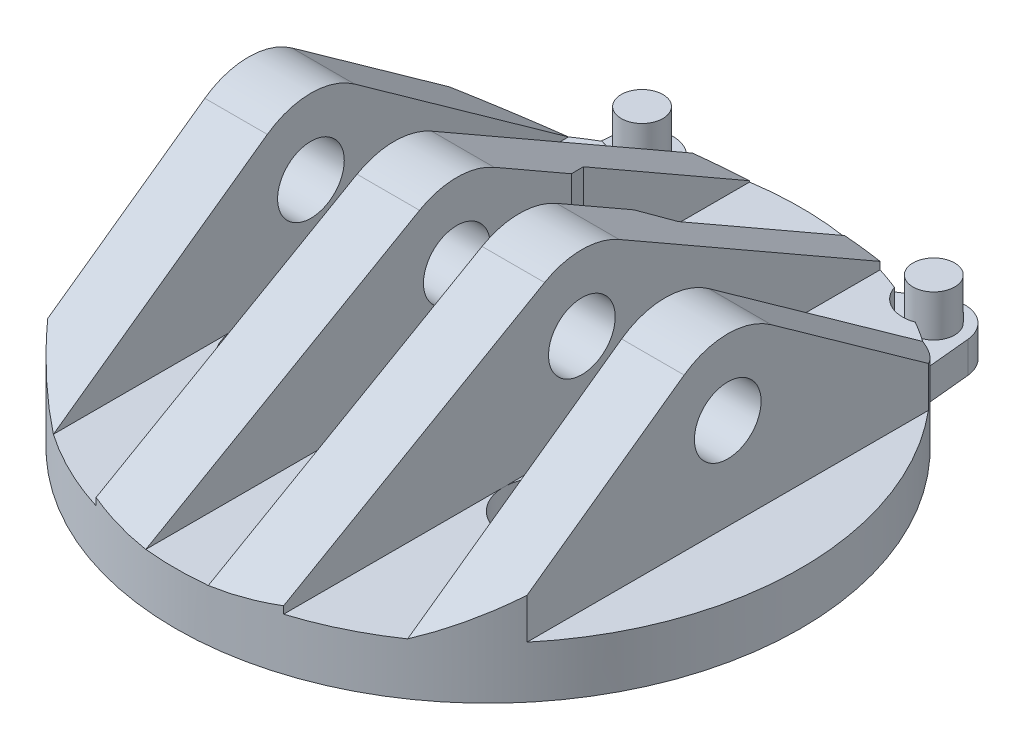
SolidWorks part; units mm, degrees
ref_plane "Front Plane" through (0, 0, 0) normal (0, 0, 1) x (1, 0, 0)
ref_plane "Top Plane" through (0, 0, 0) normal (0, 1, 0) x (1, 0, 0)
ref_plane "Right Plane" through (0, 0, 0) normal (1, 0, 0) x (0, 0, -1)
sketch "Sketch1" plane through (0, 0, 0) normal (0, 1, 0) x (1, 0, 0)
  line L0 (0, 0) -> (0, 15) construction
  line L1 (0, 0) -> (12.9904, -7.5) construction
  line L2 (0, 0) -> (-12.9904, -7.5) construction
  circle A0 centre (0, 0) radius 30
  circle A1 centre (0, 0) radius 15 construction
  circle A2 centre (0, 15) radius 2.1
  circle A3 centre (12.9904, -7.5) radius 2.1
  circle A4 centre (-12.9904, -7.5) radius 2.1
  dimension "D1" = 60
  dimension "D2" = 30
  dimension "D5" = 4.2
  dimension "D3" = 120
  dimension "D4" = 120
extrude "Boss-Extrude1" add sketch "Sketch1" along normal blind 5
sketch "Sketch2" plane through (0, 5, 0) normal (0, 1, 0) x (1, 0, 0)
  line L0 (0, 30) -> (0, -30) construction
  line L5 (17, 11) -> (17, 24.7184)
  line L6 (-3, -29.8496) -> (3, -29.8496)
  line L8 (4.1569, 15) -> (2.0785, 18.6)
  line L9 (2.0785, 18.6) -> (-2.0785, 18.6)
  line L10 (-2.0785, 18.6) -> (-4.1569, 15)
  line L11 (-4.1569, 15) -> (-2.0785, 11.4)
  line L12 (-2.0785, 11.4) -> (2.0785, 11.4)
  line L13 (2.0785, 11.4) -> (4.1569, 15)
  line L14 (-12.9904, -3.3431) -> (-16.5904, -5.4215)
  line L15 (-16.5904, -5.4215) -> (-16.5904, -9.5785)
  line L16 (-16.5904, -9.5785) -> (-12.9904, -11.6569)
  line L17 (-12.9904, -11.6569) -> (-9.3904, -9.5785)
  line L18 (-9.3904, -9.5785) -> (-9.3904, -5.4215)
  line L19 (-9.3904, -5.4215) -> (-12.9904, -3.3431)
  line L20 (12.9904, -3.3431) -> (9.3904, -5.4215)
  line L21 (9.3904, -5.4215) -> (9.3904, -9.5785)
  line L22 (9.3904, -9.5785) -> (12.9904, -11.6569)
  line L23 (12.9904, -11.6569) -> (16.5904, -9.5785)
  line L24 (16.5904, -9.5785) -> (16.5904, -5.4215)
  line L25 (16.5904, -5.4215) -> (12.9904, -3.3431)
  line L49 (-3, -29.8496) -> (-3, 11)
  line L50 (-3, 11) -> (3, 11)
  line L51 (3, -29.8496) -> (3, 11)
  line L52 (-3, -29.8496) -> (3, 11) construction
  line L53 (-3, 11) -> (3, -29.8496) construction
  line L54 (3, 11) -> (9, 11)
  line L55 (3, 11) -> (3, -28.6182)
  line L56 (3, -28.6182) -> (9, -28.6182)
  line L57 (9, 11) -> (9, -28.6182)
  line L58 (9, 11) -> (17, 11)
  line L59 (9, 11) -> (9, -24.7184)
  line L60 (9, -24.7184) -> (17, -24.7184)
  line L61 (17, 11) -> (17, -24.7184)
  line L62 (17, 19.2614) -> (23, 19.2614)
  line L63 (17, 19.2614) -> (17, -19.2614)
  line L64 (17, -19.2614) -> (23, -19.2614)
  line L65 (23, 19.2614) -> (23, -19.2614)
  line L66 (4.5569, 11) -> (4.5569, 29.6519)
  line L67 (9, 11) -> (9, 28.6182)
  line L68 (3, 11) -> (4.5569, 13.6967)
  circle A1 centre (0, 0) radius 30 construction
  circle A2 centre (0, 15) radius 3.6 construction
  circle A3 centre (-12.9904, -7.5) radius 3.6 construction
  circle A4 centre (12.9904, -7.5) radius 3.6 construction
  circle A5 centre (0, 0) radius 30
  circle A6 centre (0, 0) radius 30
  point P2 (0, -9.4248)
  point P8 (0, -9.4248)
  circle M7 centre (0, 0) radius 30
  dimension "D1" = 6
  dimension "D2" = 0.4
  dimension "D3" = 6
  dimension "D4" = 7.2
  dimension "D5" = 8
  dimension "D6" = 6
  dimension "D7" = 0
  dimension "D8" = 0.4
sketch "Sketch7" plane through (0, 5, 0) normal (0, 1, 0) x (1, 0, 0)
  circle A0 centre (0, 15) radius 4
  circle A1 centre (12.9904, -7.5) radius 4
  circle A2 centre (-12.9904, -7.5) radius 4
  dimension "D1" = 8
extrude "Cut-Extrude2" cut sketch "Sketch7" against normal blind 2
extrude "Boss-Extrude5" add sketch "Sketch2" along normal blind 16 contours L57 L54 L51 L56 | L56 L51 M7 | L64 L61 M7 | L65 L62 L61 L64 | L61 L62 L5 M7 | L54 L67 L66 M7 | L68 L54 L66
sketch "Sketch8" plane through (23, 0, 0) normal (1, 0, 0) x (0, 0, -1)
  line L0 (0, 21) -> (0, 5) construction
  line L1 (19.2614, 21) -> (-19.2614, 21) construction
  line L2 (19.2614, 5) -> (-19.2614, 5) construction
  circle A0 centre (0, 13.8) radius 3.2
  point P8 (0, 17)
  dimension "D1" = 6.4
  dimension "D2" = 4
extrude "Cut-Extrude3" cut sketch "Sketch8" against normal through all
sketch "Sketch9" plane through (3, 0, 0) normal (-1, 0, 0) x (0, 0, 1)
  line L0 (0, 21) -> (0, 5) construction
  line L1 (-29.8496, 5) -> (-3.5786, 20.0477)
  line L3 (29.8496, 21) -> (-11, 21) construction
  line L4 (29.8496, 5) -> (-11, 5) construction
  line L6 (29.8496, 5) -> (3.5786, 20.0477)
  line L8 (-13.6967, 5) -> (-11, 5) construction
  line L10 (-11, 21) -> (-13.6967, 21) construction
  line L11 (-29.6519, 5) -> (-13.6967, 5) construction
  line L12 (-13.6967, 21) -> (-29.6519, 21) construction
  line L13 (-29.6519, 21) -> (-29.6519, 5) construction
  line L14 (-11, 5) -> (29.8496, 5) construction
  line L15 (29.8496, 5) -> (29.8496, 21) construction
  line L16 (-13.6967, 5) -> (-11, 5)
  line L17 (-11, 21) -> (-13.6967, 21)
  line L18 (-29.6519, 5) -> (-13.6967, 5)
  line L19 (-13.6967, 21) -> (-29.6519, 21)
  line L20 (-29.6519, 21) -> (-29.6519, 5)
  line L21 (-11, 5) -> (29.8496, 5)
  line L22 (29.8496, 5) -> (29.8496, 21)
  line L23 (29.8496, 21) -> (-11, 21)
  circle A0 centre (0, 13.8) radius 3.2 construction
  circle A1 centre (0, 13.8) radius 3.2
  arc A2 (-3.5786, 20.0477) -> (3.5786, 20.0477) centre (0, 13.8) cw
  line M15 (29.8496, 5) -> (29.8496, 21)
  line M16 (29.8496, 21) -> (-11, 21)
  line M17 (-11, 21) -> (-11, 5)
extrude "Cut-Extrude4" cut sketch "Sketch9" against normal up to next contours L19 L20 L1 L17 M17 | L1 A2 L23 M17 | A2 L6 M16 M15
sketch "Sketch10" plane through (17, 0, 0) normal (-1, 0, 0) x (0, 0, 1)
  line L0 (0, 5.0953) -> (0, 21) construction
  line L2 (24.7184, 5) -> (4.1834, 19.6599)
  line L3 (-24.7184, 5) -> (-4.1834, 19.6599)
  line L6 (-24.7184, 5) -> (24.7184, 5)
  line L7 (24.7184, 5) -> (24.7184, 21)
  line L8 (24.7184, 21) -> (-24.7184, 21)
  line L9 (-24.7184, 21) -> (-24.7184, 5)
  line L10 (-24.7184, 5) -> (24.7184, 5)
  line L11 (24.7184, 5) -> (24.7184, 21)
  line L12 (24.7184, 21) -> (-24.7184, 21)
  line L13 (-24.7184, 21) -> (-24.7184, 5)
  circle A0 centre (0, 13.8) radius 3.2 construction
  circle A1 centre (0, 13.8) radius 3.2
  arc A2 (-4.1834, 19.6599) -> (4.1834, 19.6599) centre (0, 13.8) cw
  line M10 (24.7184, 5) -> (24.7184, 21)
  line M11 (24.7184, 21) -> (-24.7184, 21)
  line M12 (-24.7184, 21) -> (-24.7184, 5)
  dimension "D1" = 0
extrude "Cut-Extrude5" cut sketch "Sketch10" against normal up to next contours L3 A2 L12 M12 | A2 L2 M11 M10
ref_plane "Plane1" through (0, 0, 0) normal (-1, 0, 0) x (0, 0, 1)
mirror "Mirror1" about plane through (0, 0, 0) normal (-1, 0, 0) of "Cut-Extrude5", "Cut-Extrude4", "Cut-Extrude3", "Boss-Extrude5"
sketch "Sketch13" plane through (0, 0, 0) normal (0, -1, 0) x (1, 0, 0)
  line L0 (0, 0) -> (18.2639, -37.5389) construction
  line L1 (0, 0) -> (0, -39.0213) construction
  line L2 (16.986, -29.0648) -> (17.4375, -24.4117)
  line L3 (12.3851, -31.3032) -> (8.4453, -28.7867)
  line L4 (14, -28.775) -> (0, -28.775) construction
  arc A0 (12.3851, -31.3032) -> (16.986, -29.0648) centre (14, -28.775) ccw
  circle A1 centre (0, 0) radius 30 construction
  circle A3 centre (0, 0) radius 30
  circle A4 centre (0, 0) radius 30
  point P13 (15.3125, -31.4726)
  circle M1 centre (0, 0) radius 30
  dimension "D2" = 3
  dimension "D1" = 14
  dimension "D3" = 10
  dimension "D5" = 35
  dimension "D4" = 0
extrude "Boss-Extrude8" add sketch "Sketch13" against normal blind 3 contours L3 A0 L2 M1
sketch "Sketch15" plane through (0, 5, 0) normal (0, 1, 0) x (1, 0, 0)
  line L2 (9, 28.6182) -> (9, -7.2228)
  line L3 (17, -24.7184) -> (17, 24.7184)
  line L4 (9, 28.6182) -> (9, -7.2228)
  line L5 (17, -24.7184) -> (17, 24.7184)
  line L7 (9, -7.7772) -> (9, -28.6182)
  line L8 (9, -7.7772) -> (9, -28.6182)
  circle A0 centre (14, 28.775) radius 3
  arc A3 (9, -28.6182) -> (17, -24.7184) centre (0, 0) ccw
  arc A4 (17, 24.7184) -> (9, 28.6182) centre (0, 0) ccw
  arc A5 (9, -28.6182) -> (17, -24.7184) centre (0, 0) ccw
  arc A6 (17, 24.7184) -> (9, 28.6182) centre (0, 0) ccw
  arc A8 (9, -7.7772) -> (9, -7.2228) centre (12.9904, -7.5) ccw
  arc A9 (9, -7.7772) -> (9, -7.2228) centre (12.9904, -7.5) ccw
  arc M5 (17, 24.7184) -> (9, 28.6182) centre (0, 0) ccw
  dimension "D1" = 0
extrude "Cut-Extrude8" cut sketch "Sketch15" against normal up to surface (2 mm away) contours A0 M5 up to face at (14.0161, 3, -28.8081)
sketch "Sketch14" plane through (0, 3, 0) normal (0, 1, 0) x (1, 0, 0)
  line L2 (12.3851, 31.3032) -> (8.4453, 28.7867)
  line L3 (17.4375, 24.4117) -> (16.986, 29.0648)
  line L4 (12.3851, 31.3032) -> (8.4453, 28.7867)
  line L5 (17.4375, 24.4117) -> (16.986, 29.0648)
  circle A0 centre (14, 28.775) radius 2
  arc A2 (11.1452, 27.8529) -> (8.4453, 28.7867) centre (0, 0) ccw
  arc A3 (16.986, 29.0648) -> (12.3851, 31.3032) centre (14, 28.775) ccw
  arc A4 (11.1452, 27.8529) -> (8.4453, 28.7867) centre (0, 0) ccw
  arc A5 (16.986, 29.0648) -> (12.3851, 31.3032) centre (14, 28.775) ccw
  arc A9 (11.1452, 27.8529) -> (15.0364, 25.9597) centre (14, 28.775) ccw
  arc A10 (11.1452, 27.8529) -> (15.0364, 25.9597) centre (14, 28.775) ccw
  arc A11 (17.4375, 24.4117) -> (15.0364, 25.9597) centre (0, 0) ccw
  arc A12 (17.4375, 24.4117) -> (15.0364, 25.9597) centre (0, 0) ccw
  dimension "3.8" = 4
  dimension "D1" = 0
extrude "Boss-Extrude9" add sketch "Sketch14" along normal blind 4 contours A0
mirror "Mirror2" about plane through (0, 0, 0) normal (-1, 0, 0) of "Cut-Extrude8", "Boss-Extrude9", "Boss-Extrude8"
